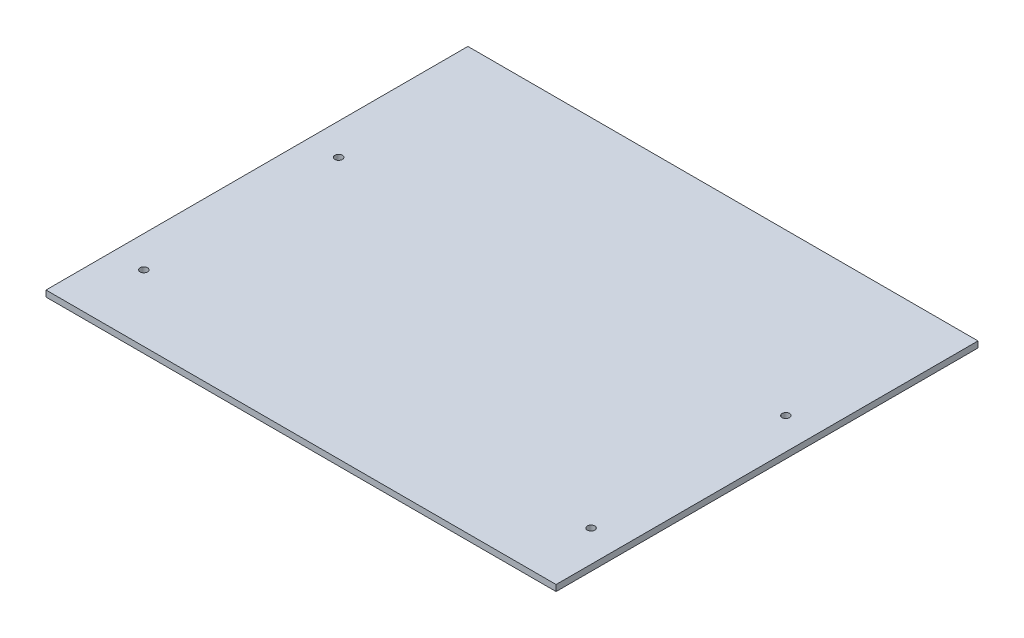
SolidWorks part; units mm, degrees
material "ABS PC"
ref_plane "Front Plane" through (0, 0, 0) normal (0, 0, 1) x (1, 0, 0)
ref_plane "Top Plane" through (0, 0, 0) normal (0, 1, 0) x (1, 0, 0)
ref_plane "Right Plane" through (0, 0, 0) normal (1, 0, 0) x (0, 0, -1)
sketch "Sketch1" plane through (0, 0, 0) normal (0, 1, 0) x (1, 0, 0)
  line L0 (231.775, 383.413) -> (231.775, 0) construction
  line L1 (0, 0) -> (463.55, 0)
  line L2 (0, 0) -> (0, 383.413)
  line L3 (0, 383.413) -> (463.55, 383.413)
  line L4 (463.55, 0) -> (463.55, 383.413)
  line L5 (28.575, 60.325) -> (28.575, 237.363) construction
  line L6 (28.575, 237.363) -> (28.575, 414.401) construction
  line L7 (434.975, 237.363) -> (434.975, 414.401) construction
  line L8 (434.975, 60.325) -> (434.975, 237.363) construction
  circle A0 centre (28.575, 60.325) radius 3.3782
  circle A1 centre (28.575, 237.363) radius 3.3782
  circle A4 centre (434.975, 237.363) radius 3.3782
  circle A5 centre (434.975, 60.325) radius 3.3782
  dimension "D3" = 6.7564
  dimension "D1" = 463.55
  dimension "D2" = 146.05
  dimension "D4" = 60.325
  dimension "D5" = 28.575
  dimension "D6" = 177.038
extrude "Boss-Extrude1" add sketch "Sketch1" along normal blind 5.588
fillet "Fillet1" [suppressed] radius 3.175
sketch "Sketch2" plane through (0, 5.588, 0) normal (0, 1, 0) x (1, 0, 0)
  line L0 (0, 367.538) -> (24.638, 367.538) construction
  line L1 (0, 383.413) -> (0, 0) construction
  line L2 (24.638, 367.538) -> (24.638, 383.413) construction
  line L3 (463.55, 383.413) -> (0, 383.413) construction
  line L4 (231.775, 383.413) -> (231.775, 0) construction
  line L5 (0, 0) -> (463.55, 0) construction
  line L6 (438.912, 367.538) -> (438.912, 383.413) construction
  line L7 (463.55, 367.538) -> (438.912, 367.538) construction
  circle A0 centre (24.638, 367.538) radius 3.3782
  circle A1 centre (438.912, 367.538) radius 3.3782
  dimension "D3" = 6.7564
  dimension "D1" = 15.875
  dimension "D2" = 24.638
extrude "Cut-Extrude1" [suppressed] cut sketch "Sketch2" against normal through all
